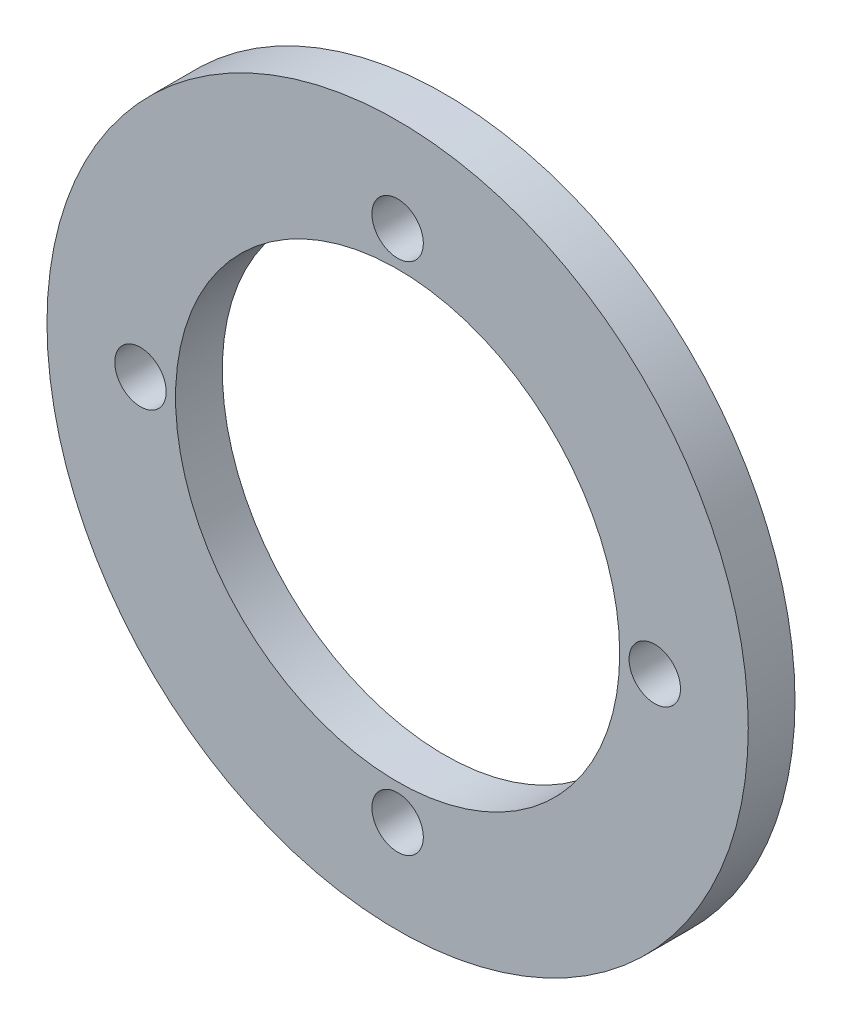
SolidWorks part; units mm, degrees
material "环氧树脂FR-4"
ref_plane "前视基准面" through (0, 0, 0) normal (0, 0, 1) x (1, 0, 0)
ref_plane "上视基准面" through (0, 0, 0) normal (0, 1, 0) x (1, 0, 0)
ref_plane "右视基准面" through (0, 0, 0) normal (1, 0, 0) x (0, 0, -1)
sketch "草图1" plane through (0, 0, 0) normal (0, 0, 1) x (1, 0, 0)
  circle A0 centre (0, 0) radius 9.5
  circle A1 centre (0, 0) radius 15
  dimension "D1" = 30
  dimension "D2" = 19
extrude "凸台-拉伸1" add sketch "草图1" along normal blind 2
sketch "草图2" plane through (0, 0, 2) normal (0, 0, 1) x (1, 0, 0)
  line L0 (0, 0) -> (0, 11) construction
  circle A0 centre (0, 11) radius 1.1
  circle A1 centre (11, 0) radius 1.1
  circle A2 centre (0, -11) radius 1.1
  circle A3 centre (-11, 0) radius 1.1
  dimension "D3" = 2.2
  dimension "D2" = 11
  dimension "D1" = 4
extrude "切除-拉伸1" cut sketch "草图2" against normal blind 2
